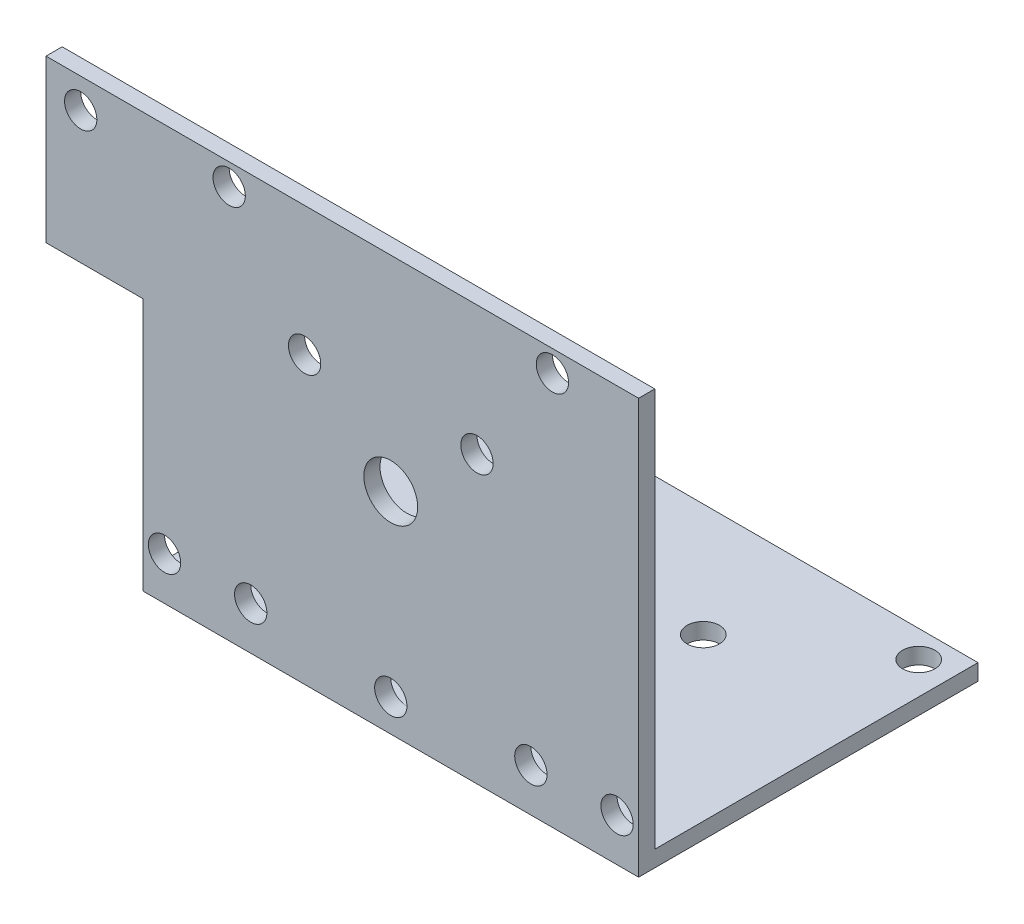
SolidWorks part; units mm, degrees
material "1060 Сплав"
ref_plane "Front" through (0, 0, 0) normal (0, 0, 1) x (1, 0, 0)
ref_plane "Top" through (0, 0, 0) normal (0, 1, 0) x (1, 0, 0)
ref_plane "Right" through (0, 0, 0) normal (1, 0, 0) x (0, 0, -1)
sketch "Эскиз1" plane through (0, 0, 0) normal (0, 0, 1) x (1, 0, 0)
  line L1 (-23, -19.25) -> (23, -19.25)
  line L2 (-23, -19.25) -> (-23, 19.25)
  line L3 (-23, 19.25) -> (23, 19.25)
  line L4 (23, -19.25) -> (23, 19.25)
  line L5 (-23, -19.25) -> (23, 19.25) construction
  line L6 (-23, 19.25) -> (23, -19.25) construction
  point P0 (0, 0)
  dimension "D1" = 38.5
  dimension "D2" = 46
extrude "Бобышка-Вытянуть1" add sketch "Эскиз1" along normal blind 1.5
sketch "Эскиз2" plane through (0, 0, 0) normal (0, 0, -1) x (-1, 0, 0)
  line L0 (23, 19.25) -> (23, -19.25) construction
  line L1 (-23, -19.25) -> (23, -19.25)
  line L2 (-23, -19.25) -> (-23, -17.75)
  line L3 (-23, -17.75) -> (23, -17.75)
  line L4 (23, -19.25) -> (23, -17.75)
  dimension "D1" = 1.5
extrude "Бобышка-Вытянуть2" add sketch "Эскиз2" along normal blind 30
sketch "Эскиз3" plane through (0, -17.75, 0) normal (0, 1, 0) x (1, 0, 0)
  line L0 (0, 30) -> (0, 0) construction
  line L1 (-23, 30) -> (23, 30) construction
  line L2 (23, 0) -> (-23, 0) construction
  line L3 (-8, 4.5) -> (8, 4.5) construction
  line L4 (-8, 4.5) -> (-8, 19.5) construction
  line L5 (-8, 19.5) -> (8, 19.5) construction
  line L6 (8, 4.5) -> (8, 19.5) construction
  line L7 (-8, 4.5) -> (8, 19.5) construction
  line L8 (-8, 19.5) -> (8, 4.5) construction
  line L9 (-20, 27.5) -> (20, 27.5) construction
  circle A0 centre (-8, 19.5) radius 1.5
  circle A1 centre (8, 19.5) radius 1.5
  circle A2 centre (-8, 4.5) radius 1.5
  circle A3 centre (8, 4.5) radius 1.5
  circle A4 centre (-20, 27.5) radius 1.5
  circle A5 centre (20, 27.5) radius 1.5
  point P5 (0, 12)
  point P19 (0, 27.5)
  dimension "D3" = 12
  dimension "D1" = 16
  dimension "D2" = 15
  dimension "D4" = 40
  dimension "D5" = 2.5
extrude "Вырез-Вытянуть1" cut sketch "Эскиз3" against normal up to next
sketch "Эскиз4" plane through (0, 0, 1.5) normal (0, 0, 1) x (1, 0, 0)
  line L0 (-15, 17.25) -> (15, 17.25) construction
  line L1 (0, 19.25) -> (0, -19.25) construction
  line L2 (23, 19.25) -> (-23, 19.25) construction
  line L3 (-23, -19.25) -> (23, -19.25) construction
  line L4 (0, 7.25) -> (-8, 7.25) construction
  line L5 (-23, 19.25) -> (-23, -19.25) construction
  circle A0 centre (-15, 17.25) radius 1.5
  circle A1 centre (15, 17.25) radius 1.5
  circle A2 centre (-8, 7.25) radius 1.5
  circle A3 centre (8, 7.25) radius 1.5
  circle A4 centre (0, 0.25) radius 2.5
  circle A6 centre (0, -16.25) radius 1.5
  circle A7 centre (-21, -15.25) radius 1.5
  circle A8 centre (21, -15.25) radius 1.5
  circle A9 centre (-13, -15.25) radius 1.5
  circle A10 centre (13, -15.25) radius 1.5
  point P10 (0, 17.25)
  point P30 (0, 0)
  dimension "D1" = 2
  dimension "D4" = 26.5
  dimension "D5" = 19
  dimension "D7" = 3
  dimension "D8" = 2
  dimension "D9" = 8
  dimension "D2" = 30
  dimension "D3" = 8
  dimension "D6" = 23
  dimension "D10" = 4
extrude "Вырез-Вытянуть2" cut sketch "Эскиз4" against normal up to next
sketch "Эскиз5" plane through (0, 0, 0) normal (0, 0, -1) x (-1, 0, 0)
  line L1 (23, 19.25) -> (32, 19.25)
  line L2 (23, 19.25) -> (23, 4.25)
  line L3 (23, 4.25) -> (32, 4.25)
  line L4 (32, 19.25) -> (32, 4.25)
  circle A0 centre (28.78, 16.5) radius 1.5
  arc A1 (15, 18.75) -> (14.9881, 16.2501) centre (15, 17.5) cw construction
  circle A2 centre (15, 17.25) radius 1.5 construction
  dimension "D3" = 13.78
  dimension "D1" = 9
  dimension "D2" = 15
  dimension "D4" = 1
extrude "Бобышка-Вытянуть3" add sketch "Эскиз5" against normal blind 1.5
